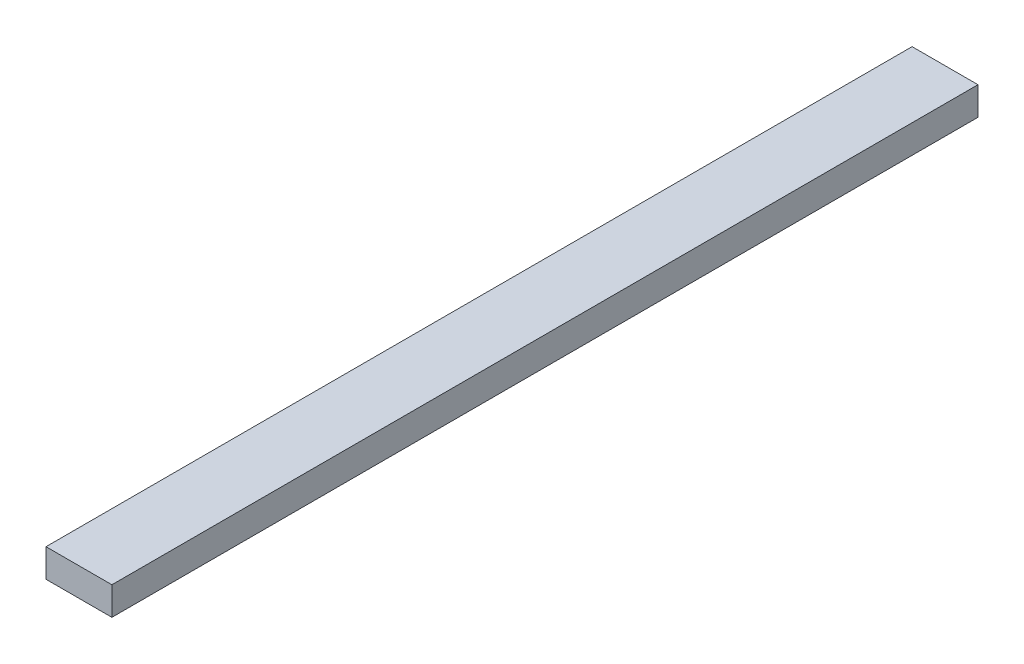
SolidWorks part; units mm, degrees
ref_plane "Front Plane" through (0, 0, 0) normal (0, 0, 1) x (1, 0, 0)
ref_plane "Top Plane" through (0, 0, 0) normal (0, 1, 0) x (1, 0, 0)
ref_plane "Right Plane" through (0, 0, 0) normal (1, 0, 0) x (0, 0, -1)
sketch "Sketch1" plane through (0, 0, 0) normal (0, 0, 1) x (1, 0, 0)
  line L1 (44.45, 19.05) -> (-44.45, 19.05)
  line L2 (44.45, 19.05) -> (44.45, -19.05)
  line L3 (44.45, -19.05) -> (-44.45, -19.05)
  line L4 (-44.45, 19.05) -> (-44.45, -19.05)
  line L5 (44.45, 19.05) -> (-44.45, -19.05) construction
  line L6 (44.45, -19.05) -> (-44.45, 19.05) construction
  point P0 (0, 0)
  dimension "D1" = 88.9
  dimension "D2" = 38.1
extrude "Boss-Extrude1" add sketch "Sketch1" along normal mid plane 1168.4
